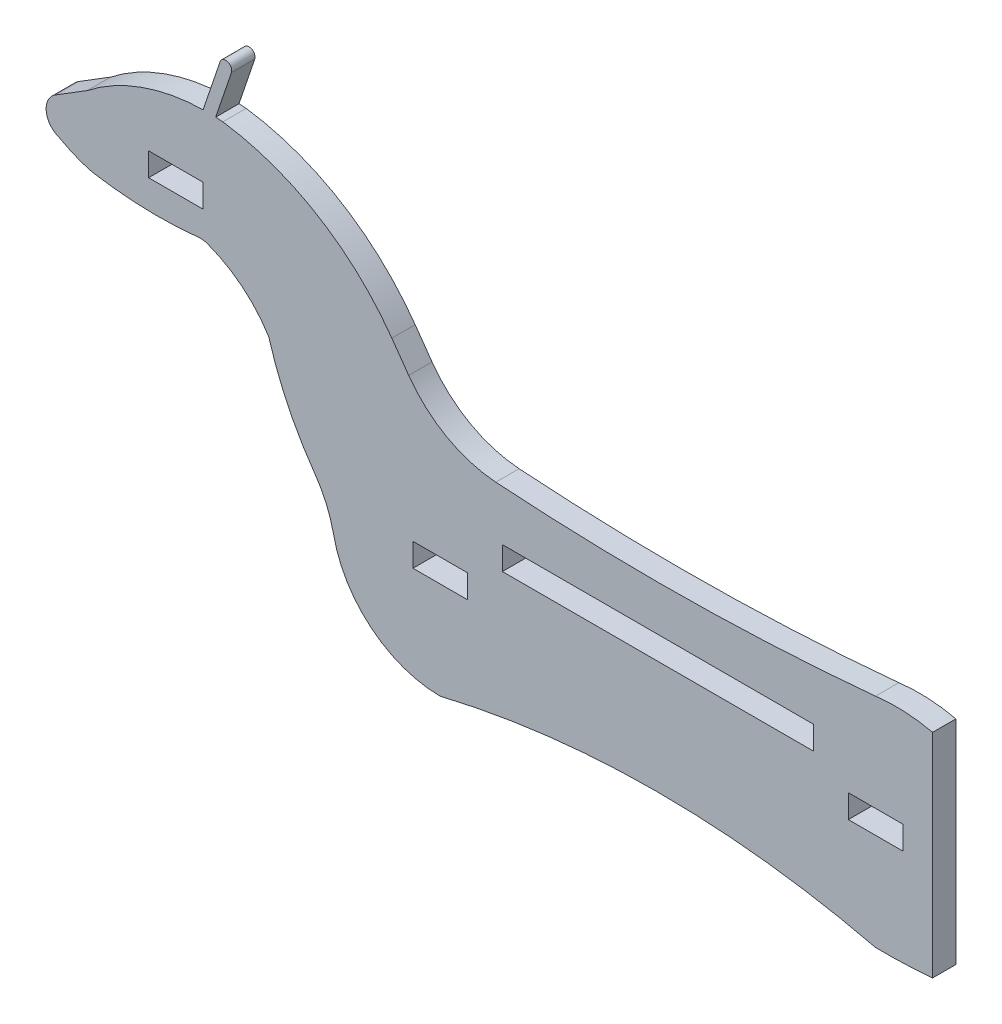
SolidWorks part; units mm, degrees
ref_plane "Alzado" through (0, 0, 0) normal (0, 0, 1) x (1, 0, 0)
ref_plane "Planta" through (0, 0, 0) normal (0, 1, 0) x (1, 0, 0)
ref_plane "Vista lateral" through (0, 0, 0) normal (1, 0, 0) x (0, 0, -1)
sketch "Croquis1" plane through (0, 0, 0) normal (0, 0, 1) x (1, 0, 0)
  line L0 (0, 0) -> (56, 0) construction
  line L1 (0, 0) -> (0, 14) construction
  line L2 (0, 0) -> (0, -14) construction
  line L3 (56, 0) -> (56, 14) construction
  line L4 (56, 0) -> (56, -14) construction
  line L5 (0, 0) -> (-14, 0) construction
  line L6 (-6.2167, 22.7727) -> (-4.044, 19.7067)
  line L7 (-29.9548, 35.2747) -> (-27.581, 42.2747) construction
  line L9 (56, 14) -> (63.3311, 12.3082) construction
  line L10 (-37.5, 28) -> (-30.5, 28)
  line L11 (-37.5, 28) -> (-37.5, 25)
  line L12 (-14, 0) -> (-14, 66.88) construction
  line L13 (-45.4, 30.7623) -> (-49.5036, 28.2164)
  line L15 (-3.5, 1.5) -> (3.5, 1.5)
  line L16 (-3.5, 1.5) -> (-3.5, -1.5)
  line L17 (-3.5, -1.5) -> (3.5, -1.5)
  line L18 (3.5, 1.5) -> (3.5, -1.5)
  line L19 (-3.5, 1.5) -> (3.5, -1.5) construction
  line L20 (-3.5, -1.5) -> (3.5, 1.5) construction
  line L25 (52.5, 1.5) -> (59.5, 1.5)
  line L26 (52.5, 1.5) -> (52.5, -1.5)
  line L27 (52.5, -1.5) -> (59.5, -1.5)
  line L28 (59.5, 1.5) -> (59.5, -1.5)
  line L29 (52.5, 1.5) -> (59.5, -1.5) construction
  line L30 (52.5, -1.5) -> (59.5, 1.5) construction
  line L43 (8, 6.8839) -> (48, 6.8839)
  line L44 (8, 6.8839) -> (8, 3.8839)
  line L45 (8, 3.8839) -> (48, 3.8839)
  line L46 (48, 6.8839) -> (48, 3.8839)
  line L48 (-30.684, 35.522) -> (-28.3102, 42.522)
  line L49 (-29.2255, 35.0275) -> (-26.8518, 42.0275)
  line L50 (63.3311, 13.6372) -> (63.3311, -13.7275)
  line L51 (-37.5, 25) -> (-30.5, 25)
  line L52 (63.3311, -13.4361) -> (56, -14) construction
  line L53 (-30.5, 28) -> (-30.5, 25)
  line L54 (-37.5, 28) -> (-30.5, 25) construction
  line L55 (-37.5, 25) -> (-30.5, 28) construction
  circle A0 centre (0, 0) radius 7
  circle A1 centre (56, 0) radius 7
  arc A2 (-27.1021, 20.0505) -> (-25.1943, 35.4919) centre (-28, 28) ccw
  arc A3 (0, -14) -> (56, -14) centre (28, -130.6876) cw
  arc A4 (-13.7082, -2.8432) -> (0, -14) centre (0, 0) ccw
  arc A5 (7.1522, 13.4157) -> (56, 14) centre (28, 312.6905) ccw
  arc A6 (56, 14) -> (63.3311, 13.6372) centre (58.6537, -6.6286) cw
  arc A9 (56, -14) -> (63.3311, -13.7275) centre (56.9755, 58.4981) ccw
  arc A13 (-22.0438, 15.0038) -> (-16.1546, 2.7797) centre (17.1027, 26.3329) ccw
  arc A14 (-22.0438, 15.0038) -> (-29.9449, 21.4342) centre (-35.3415, 6.734) ccw
  arc A16 (-40.3552, 21.4544) -> (-45.4, 30.7623) centre (-44, 25.5) ccw
  arc A18 (-45.4, 30.7623) -> (-27.9552, 35.9999) centre (-29.9826, 11.0822) cw
  arc A19 (-49.5036, 28.2164) -> (-49.1206, 23.7734) centre (-48.1856, 26.092) ccw
  arc A20 (-44.7553, 22) -> (-31.0686, 21.5735) centre (-36.356, 71.724) ccw
  arc A21 (-29.9449, 21.4342) -> (-31.0686, 21.5735) centre (-30.8065, 19.0873) ccw
  arc A22 (-48.8256, 23.6314) -> (-44.7553, 22) centre (-40.7023, 38.0057) ccw
  arc A23 (-48.8256, 23.6314) -> (-49.1206, 23.7734) centre (-50.0556, 21.4549) ccw
  arc A24 (-48.093, 29.0915) -> (-49.1866, 23.8414) centre (-44, 25.5) ccw
  arc A25 (-27.9552, 35.9999) -> (-6.2167, 22.7727) centre (-32.3654, 4.2748) cw
  arc A27 (-4.044, 19.7067) -> (7.1522, 13.4157) centre (8.1946, 28.3795) ccw
  arc A28 (-16.1546, 2.7797) -> (-13.7082, -2.8432) centre (-28.3957, -5.8896) cw
  arc A31 (-30.684, 35.522) -> (-29.2255, 35.0275) centre (-29.9548, 35.2747) ccw
  arc A32 (-26.8518, 42.0275) -> (-28.3102, 42.522) centre (-27.581, 42.2747) ccw
  arc A33 (-27.9552, 35.9999) -> (-32.5753, 21.4375) centre (-28, 28) ccw
  point P16 (-34, 26.5)
  point P31 (-22.0438, 15.0038)
  point P33 (-20, 28)
  point P47 (0, 14.5597)
  point P72 (-28.7679, 38.7747)
  dimension "D1" = 14
  dimension "D2" = 14
  dimension "D4" = 16
  dimension "D11" = 120
  dimension "D13" = 14
  dimension "D14" = 300
  dimension "D23" = 72.5047
  dimension "D24" = 20.7986
  dimension "D30" = 7
  dimension "D31" = 25
  dimension "D32" = 2.5
  dimension "D33" = 2.5
  dimension "D34" = 2.5
  dimension "D35" = 15
  dimension "D36" = 15
  dimension "D40" = 0.77
  dimension "D48" = 9.1402
  dimension "D3" = 56
  dimension "D5" = 28
  dimension "D6" = 28
  dimension "D7" = 14
  dimension "D8" = 14
  dimension "D9" = 14
  dimension "D10" = 14
  dimension "D12" = 14
  dimension "D15" = 16
  dimension "D16" = 7
  dimension "D17" = 7
  dimension "D18" = 3
  dimension "D19" = 6
  dimension "D20" = 0
  dimension "D37" = 3
  dimension "D38" = 7
  dimension "D39" = 3
  dimension "D41" = 7.2747
  dimension "D42" = 40
  dimension "D44" = 3
  dimension "D45" = 8
  dimension "D46" = 1.9548
  dimension "D47" = 7.3915
extrude "Saliente-Extruir2" add sketch "Croquis1" along normal blind 3 contours A18 A25 L6 A27 A5 A6 L50 A9 A3 A4 A28 A13 A14 A21 A20 A22 A23 A19 L13 | L16 L15 L18 L17 | L26 L25 L28 L27 | L44 L43 L46 L45 | L11 L10 L53 L51 | L49 A32 L48 A31
